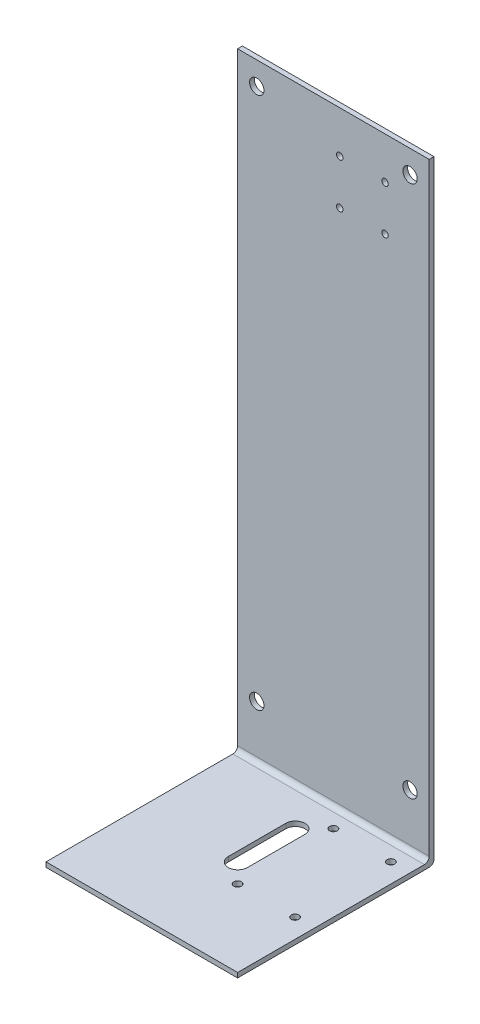
SolidWorks part; units mm, degrees
ref_plane "Front Plane" through (0, 0, 0) normal (0, 0, 1) x (1, 0, 0)
ref_plane "Top Plane" through (0, 0, 0) normal (0, 1, 0) x (1, 0, 0)
ref_plane "Right Plane" through (0, 0, 0) normal (1, 0, 0) x (0, 0, -1)
sketch "Sketch2" plane through (0, 0, 0) normal (0, 0, 1) x (1, 0, 0)
  line L1 (-63.5, -203.2) -> (63.5, -203.2)
  line L2 (-63.5, -203.2) -> (-63.5, 203.2)
  line L3 (-63.5, 203.2) -> (63.5, 203.2)
  line L4 (63.5, -203.2) -> (63.5, 203.2)
  line L5 (-63.5, -203.2) -> (63.5, 203.2) construction
  line L6 (-63.5, 203.2) -> (63.5, -203.2) construction
  point P0 (0, 0)
  dimension "D1" = 127
  dimension "D2" = 406.4
extrude "Boss-Extrude1" add sketch "Sketch2" along normal blind 3.175
sketch "Sketch3" plane through (0, 0, 3.175) normal (0, 0, 1) x (1, 0, 0)
  line L0 (63.5, -203.2) -> (63.5, 203.2) construction
  line L1 (-63.5, -203.2) -> (63.5, -203.2)
  line L2 (-63.5, -203.2) -> (-63.5, -200.025)
  line L3 (-63.5, -200.025) -> (63.5, -200.025)
  line L4 (63.5, -203.2) -> (63.5, -200.025)
  dimension "D1" = 3.175
extrude "Boss-Extrude2" add sketch "Sketch3" along normal blind 127
fillet "Fillet1" radius 3.175 2 edges at (0, -203.2, 0) (0, -200.025, 3.175)
sketch "Sketch4" plane through (0, -200.025, 0) normal (0, 1, 0) x (1, 0, 0)
  line L2 (6.5329, -66.675) -> (6.5329, -28.575)
  line L4 (-6.1671, -66.675) -> (-6.1671, -28.575)
  circle A0 centre (12.7, -79.375) radius 2.54
  circle A1 centre (50.8, -79.375) radius 2.54
  circle A2 centre (50.8, -15.875) radius 2.54
  circle A3 centre (12.7, -15.875) radius 2.54
  arc A7 (6.5329, -28.575) -> (-6.1671, -28.575) centre (0.1829, -28.575) ccw
  arc A8 (-6.1671, -66.675) -> (6.5329, -66.675) centre (0.1829, -66.675) ccw
  spline S0 degree 2 poles (4.4088, -26.3162) (3.8704, -26.3162) (3.2298, -26.5366) (2.6982, -26.7195) (2.1398, -27.0409) (1.1422, -27.6152) (0.2495, -28.5078) (-0.6406, -29.3979) (-1.2152, -30.3948) (-1.5365, -30.9524) (-1.7203, -31.4856) (-1.9412, -32.1266) (-1.9412, -32.6662) knots 0 0 0 0.125 0.125 0.25 0.25 0.5 0.5 0.75 0.75 0.875 0.875 1 1 1 construction
  point P24 (2.1907, -61.9442)
  dimension "D4" = 12.7
extrude "Cut-Extrude1" cut sketch "Sketch4" against normal through all
sketch "Sketch5" plane through (0, 0, 3.175) normal (0, 0, 1) x (1, 0, 0)
  line L0 (63.5, -196.85) -> (63.5, 203.2) construction
  line L6 (63.5, 203.2) -> (-63.5, 203.2) construction
  circle A0 centre (-50.8, 187.96) radius 4.7625
  circle A1 centre (50.8, 187.96) radius 4.7625
  circle A2 centre (-50.8, -165.1) radius 4.7625
  circle A3 centre (50.8, -165.1) radius 4.7625
  circle A4 centre (34.2087, 175.39) radius 2.15
  circle A5 centre (4.2088, 175.39) radius 2.15
  circle A6 centre (4.2088, 145.69) radius 2.15
  circle A7 centre (34.2087, 145.69) radius 2.15
  point P24 (0, 0)
  point P26 (0, 0)
  point P27 (0, 0)
  point P28 (0, 0)
  dimension "D3" = 4.3
  dimension "D5" = 114.3
  dimension "D2" = 368.3
  dimension "D6" = 9.525
  dimension "D4" = 29.2913
  dimension "D1" = 12.7
  dimension "D7" = 15.24
  dimension "D8" = 59.2912
  dimension "D9" = 27.81
  dimension "D10" = 57.51
extrude "Cut-Extrude2" cut sketch "Sketch5" against normal through all
